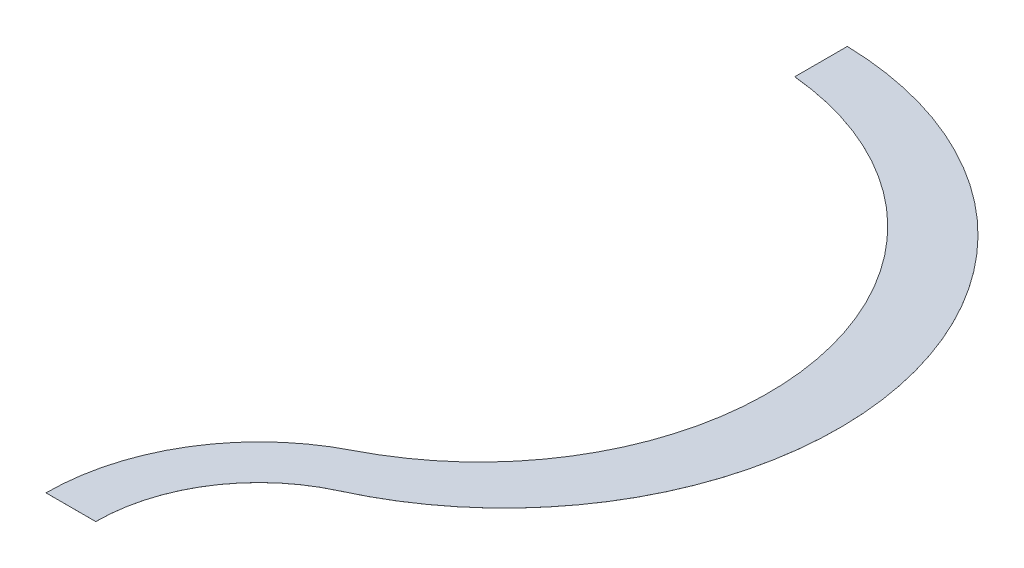
SolidWorks part; units mm, degrees
ref_plane "Plano frontal" through (0, 0, 0) normal (0, 0, 1) x (1, 0, 0)
ref_plane "Plano superior" through (0, 0, 0) normal (0, 1, 0) x (1, 0, 0)
ref_plane "Plano direito" through (0, 0, 0) normal (1, 0, 0) x (0, 0, -1)
sketch "Esboço1" plane through (0, 0, 0) normal (0, 1, 0) x (1, 0, 0)
  line L0 (-1093, 595.536) -> (-1073, 595.536)
  line L1 (0, 0) -> (18.9344, 0)
  line L2 (0, 0) -> (0, 766.8662)
  line L3 (0, 766.8662) -> (18.9344, 766.8662)
  line L4 (18.9344, 0) -> (18.9344, 766.8662)
  line L5 (-381.6968, 766.8662) -> (-362.7624, 766.8662)
  line L6 (-381.6968, 766.8662) -> (-381.6968, 345.536)
  line L7 (-381.6968, 345.536) -> (-362.7624, 345.536)
  line L8 (-362.7624, 766.8662) -> (-362.7624, 345.536)
  line L9 (-858.9344, 645.536) -> (-840, 645.536)
  line L10 (-858.9344, 645.536) -> (-858.9344, 345.536)
  line L11 (-858.9344, 345.536) -> (-840, 345.536)
  line L12 (-840, 645.536) -> (-840, 345.536)
  line L13 (-853.5858, 925.2213) -> (-1253.5858, 925.2213)
  line L14 (-853.5858, 925.2213) -> (-853.5858, 945.2213)
  line L15 (-853.5858, 945.2213) -> (-1253.5858, 945.2213)
  line L16 (-1253.5858, 925.2213) -> (-1253.5858, 945.2213)
  line L17 (-1093, 595.536) -> (-1093, 195.536)
  line L18 (-1093, 195.536) -> (-1073, 195.536)
  line L19 (-1073, 595.536) -> (-1073, 195.536)
  line L21 (-858.9344, 427.7897) -> (-1250.0103, 427.7897)
  line L23 (-858.9344, 407.7897) -> (-1250.0103, 407.7897)
  line L24 (-1250.0103, 427.7897) -> (-1250.0103, 407.7897)
  line L33 (-1439.6613, 239.7512) -> (-1560.0448, 239.7512)
  line L34 (-1439.6613, 239.7512) -> (-1439.6613, 219.7512)
  line L35 (-1439.6613, 219.7512) -> (-1560.0448, 219.7512)
  line L36 (-1560.0448, 239.7512) -> (-1560.0448, 219.7512)
  line L37 (-1627.2015, 576.144) -> (-1607.2015, 576.144)
  line L38 (-1627.2015, 576.144) -> (-1627.2015, 317.0654)
  line L39 (-1627.2015, 317.0654) -> (-1607.2015, 317.0654)
  line L40 (-1607.2015, 576.144) -> (-1607.2015, 317.0654)
  line L41 (-1627.2015, 769.6927) -> (-1607.2015, 769.6927)
  line L42 (-1627.2015, 769.6927) -> (-1627.2015, 1019.6927)
  line L43 (-1627.2015, 1019.6927) -> (-1607.2015, 1019.6927)
  line L44 (-1607.2015, 769.6927) -> (-1607.2015, 1019.6927)
  line L45 (297.667, 791.25) -> (316.6014, 791.25)
  line L46 (303.0156, 1070.9353) -> (303.0156, 1090.9353)
  arc A6 (-381.6968, 766.8662) -> (18.9344, 766.8662) centre (-181.3812, 766.8662) cw
  arc A7 (-362.7624, 766.8662) -> (0, 766.8662) centre (-181.3812, 766.8662) cw
  arc A8 (-362.7624, 345.536) -> (-858.9344, 345.536) centre (-610.8484, 345.536) cw
  arc A9 (-381.6968, 345.536) -> (-840, 345.536) centre (-610.8484, 345.536) cw
  arc A10 (-840, 645.536) -> (-803.6955, 702.0415) centre (-777.8744, 645.536) cw
  arc A11 (-803.6955, 702.0415) -> (-853.5858, 945.2213) centre (-856.6336, 817.8884) ccw
  arc A12 (-858.9344, 645.536) -> (-814.4955, 717.9247) centre (-777.7563, 645.536) cw
  arc A13 (-814.4955, 717.9247) -> (-853.5858, 925.2213) centre (-864.2122, 815.8835) ccw
  arc A14 (-1093, 595.536) -> (-1188.5366, 677.9223) centre (-1176.2913, 595.536) ccw
  arc A15 (-1188.5366, 677.9223) -> (-1354.3411, 742.8189) centre (-1214.8489, 854.9525) cw
  arc A16 (-1354.3411, 742.8189) -> (-1253.5858, 945.2213) centre (-1257.3278, 820.805) cw
  arc A17 (-1073, 595.536) -> (-1188.5366, 698.0004) centre (-1176.2038, 595.536) ccw
  arc A18 (-1188.5366, 698.0004) -> (-1341.8208, 766.8662) centre (-1207.9995, 859.705) cw
  arc A19 (-1341.8208, 766.8662) -> (-1253.5858, 925.2213) centre (-1258.876, 824.4093) cw
  arc A22 (-1368.7558, 309.7722) -> (-1439.6613, 219.7512) centre (-1474.849, 320.402) cw
  arc A23 (-1388.5562, 309.7722) -> (-1439.6613, 239.7512) centre (-1477.6183, 321.1143) cw
  arc A24 (-1388.5562, 309.7722) -> (-1250.0103, 427.7897) centre (-1254.4723, 292.6965) cw
  arc A25 (-1607.2015, 317.0654) -> (-1560.0448, 239.7512) centre (-1520.2441, 317.0654) ccw
  arc A26 (-1627.2015, 317.0654) -> (-1560.0448, 219.7512) centre (-1523.1159, 317.0654) ccw
  arc A27 (-1368.7558, 309.7722) -> (-1250.0103, 407.7897) centre (-1259.9289, 298.8686) cw
  arc A28 (316.6014, 791.25) -> (352.9059, 847.7554) centre (378.727, 791.25) cw
  arc A29 (352.9059, 847.7554) -> (303.0156, 1090.9353) centre (299.9678, 963.6023) ccw
  arc A30 (297.667, 791.25) -> (342.1059, 863.6386) centre (378.845, 791.25) cw
  arc A31 (342.1059, 863.6386) -> (303.0156, 1070.9353) centre (292.3891, 961.5974) ccw
extrude "Ressalto-extrusão10" add sketch "Esboço1" along normal blind 0.01 contours A31 L46 A29 A28 L45 A30
